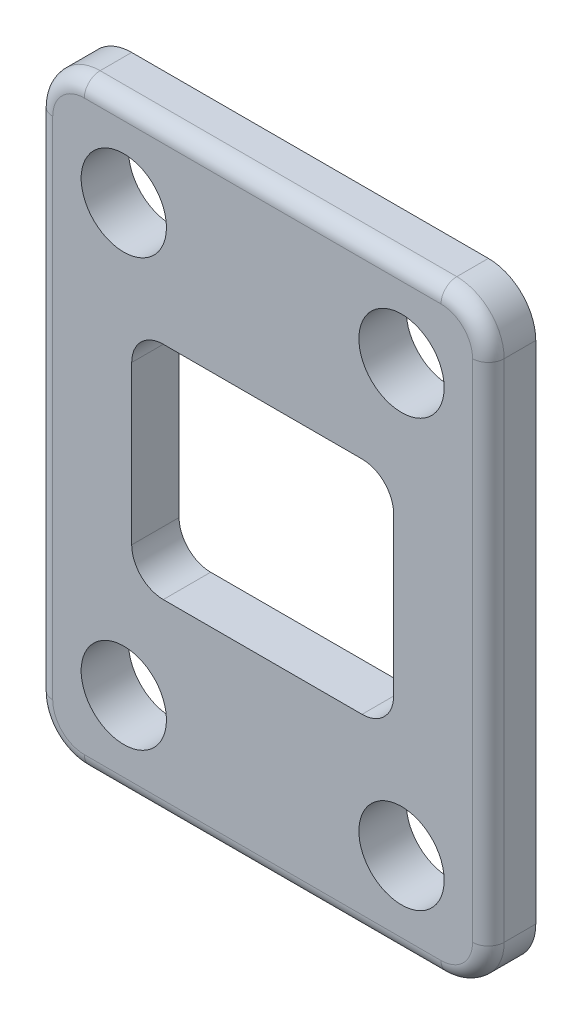
SolidWorks part; units mm, degrees
ref_plane "前视基准面" through (0, 0, 0) normal (0, 0, 1) x (1, 0, 0)
ref_plane "上视基准面" through (0, 0, 0) normal (0, 1, 0) x (1, 0, 0)
ref_plane "右视基准面" through (0, 0, 0) normal (1, 0, 0) x (0, 0, -1)
sketch "草图1" plane through (0, 0, 0) normal (0, 0, 1) x (1, 0, 0)
  line L0 (97.5198, 11.5) -> (86.228, 11.5) construction
  line L1 (84.728, 10) -> (84.728, 7) construction
  line L3 (99.0198, 7) -> (99.0198, 10) construction
  line L4 (99.0198, -6) -> (99.0198, -3) construction
  line L6 (84.728, -3) -> (84.728, -6) construction
  line L7 (86.228, -7.5) -> (97.5198, -7.5) construction
  line L8 (97.5198, 11.5) -> (86.228, 11.5)
  line L9 (84.728, 10) -> (84.728, 7)
  line L11 (99.0198, 7) -> (99.0198, 10)
  line L12 (99.0198, -6) -> (99.0198, -3)
  line L14 (84.728, -3) -> (84.728, -6)
  line L15 (86.228, -7.5) -> (97.5198, -7.5)
  line L17 (99.0198, 7) -> (99.0198, -3)
  line L18 (84.728, 7) -> (84.728, -3)
  line L20 (88.728, 5.5) -> (95.0198, 5.5)
  line L21 (87.728, 4.5) -> (87.728, -0.5)
  line L22 (88.728, -1.5) -> (95.0198, -1.5)
  line L23 (96.0198, 4.5) -> (96.0198, -0.5)
  line L24 (87.728, 5.5) -> (96.0198, -1.5) construction
  line L25 (87.728, -1.5) -> (96.0198, 5.5) construction
  arc A0 (99.0198, 10) -> (97.5198, 11.5) centre (97.5198, 10) ccw construction
  arc A1 (86.228, 11.5) -> (84.728, 10) centre (86.228, 10) ccw construction
  arc A2 (97.5198, -7.5) -> (99.0198, -6) centre (97.5198, -6) ccw construction
  arc A3 (84.728, -6) -> (86.228, -7.5) centre (86.228, -6) ccw construction
  arc A4 (99.0198, 10) -> (97.5198, 11.5) centre (97.5198, 10) ccw
  arc A5 (86.228, 11.5) -> (84.728, 10) centre (86.228, 10) ccw
  arc A6 (97.5198, -7.5) -> (99.0198, -6) centre (97.5198, -6) ccw
  arc A7 (84.728, -6) -> (86.228, -7.5) centre (86.228, -6) ccw
  circle A8 centre (87.478, -4.75) radius 1.35 construction
  circle A9 centre (96.2698, -4.75) radius 1.35 construction
  circle A10 centre (96.2698, 8.75) radius 1.35 construction
  circle A11 centre (87.478, 8.75) radius 1.35 construction
  circle A12 centre (87.478, -4.75) radius 1.35
  circle A13 centre (96.2698, -4.75) radius 1.35
  circle A14 centre (96.2698, 8.75) radius 1.35
  circle A15 centre (87.478, 8.75) radius 1.35
  arc A16 (88.728, 5.5) -> (87.728, 4.5) centre (88.728, 4.5) ccw
  arc A17 (87.728, -0.5) -> (88.728, -1.5) centre (88.728, -0.5) ccw
  arc A18 (95.0198, -1.5) -> (96.0198, -0.5) centre (95.0198, -0.5) ccw
  arc A19 (95.0198, 5.5) -> (96.0198, 4.5) centre (95.0198, 4.5) cw
  point P28 (91.8739, 2)
  dimension "D5" = 1
  dimension "D1" = 3
  dimension "D2" = 3
  dimension "D3" = 6
  dimension "D4" = 6
extrude "凸台-拉伸2" add sketch "草图1" along normal blind 1.5
fillet "圆角1" radius 0.5 8 edges at (85.1674, 11.0607, 1.5) (91.8739, 11.5, 1.5) (98.5804, 11.0607, 1.5) (99.0198, 2, 1.5) (98.5804, -7.0607, 1.5) (91.8739, -7.5, 1.5) (85.1674, -7.0607, 1.5) (84.728, 2, 1.5)
